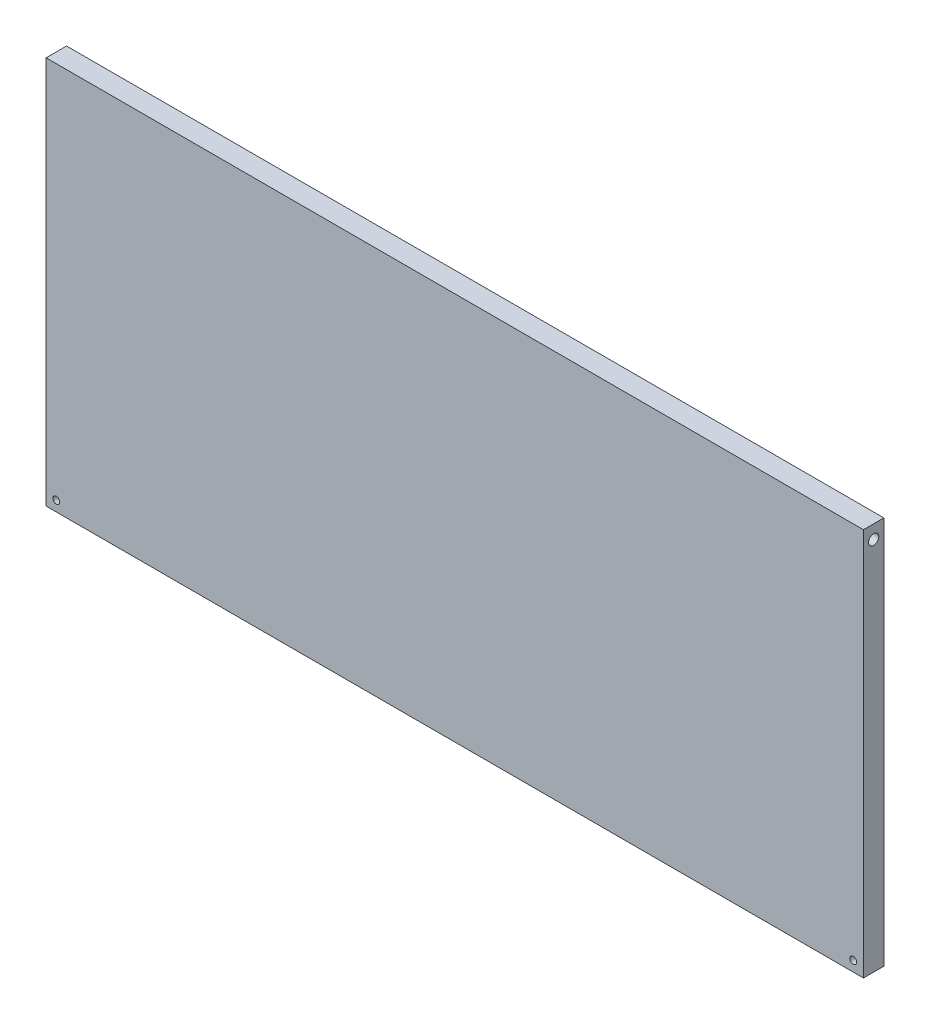
SolidWorks part; units mm, degrees
ref_plane "前视基准面" through (0, 0, 0) normal (0, 0, 1) x (1, 0, 0)
ref_plane "上视基准面" through (0, 0, 0) normal (0, 1, 0) x (1, 0, 0)
ref_plane "右视基准面" through (0, 0, 0) normal (1, 0, 0) x (0, 0, -1)
other "Configuration Table"
sketch "草图1" plane through (0, 0, 0) normal (0, 0, 1) x (1, 0, 0)
  line L1 (0, 0) -> (120, 0)
  line L2 (0, 0) -> (0, 57)
  line L3 (0, 57) -> (120, 57)
  line L4 (120, 0) -> (120, 57)
  dimension "D1" = 120
  dimension "D2" = 57
extrude "凸台-拉伸1" add sketch "草图1" along normal blind 3
ref_plane "基准面1" through (120, 0, 0) normal (1, 0, 0) x (0, 0, -1)
sketch "草图2" plane through (120, 0, 0) normal (1, 0, 0) x (0, 0, -1)
  line L0 (-3, 57) -> (0, 57) construction
  line L1 (-3, 0) -> (-3, 57) construction
  circle A0 centre (-1.5, 55) radius 0.75
  dimension "D1" = 1.5
  dimension "D2" = 2
  dimension "D3" = 1.5
extrude "切除-拉伸1" cut sketch "草图2" against normal blind 124
ref_plane "基准面2" through (0, 0, 3) normal (0, 0, 1) x (1, 0, 0)
sketch "草图3" plane through (0, 0, 3) normal (0, 0, 1) x (1, 0, 0)
  line L0 (0, 57) -> (0, 0) construction
  line L1 (0, 0) -> (120, 0) construction
  line L2 (120, 0) -> (120, 57) construction
  circle A0 centre (1.5, 1.5) radius 0.5
  circle A1 centre (118.5, 1.5) radius 0.5
  point P10 (0, 0)
  dimension "D1" = 1
  dimension "D4" = 1
  dimension "D2" = 1.5
  dimension "D3" = 1.5
  dimension "D5" = 1.5
  dimension "D6" = 1.5
extrude "切除-拉伸2" cut sketch "草图3" against normal blind 10
